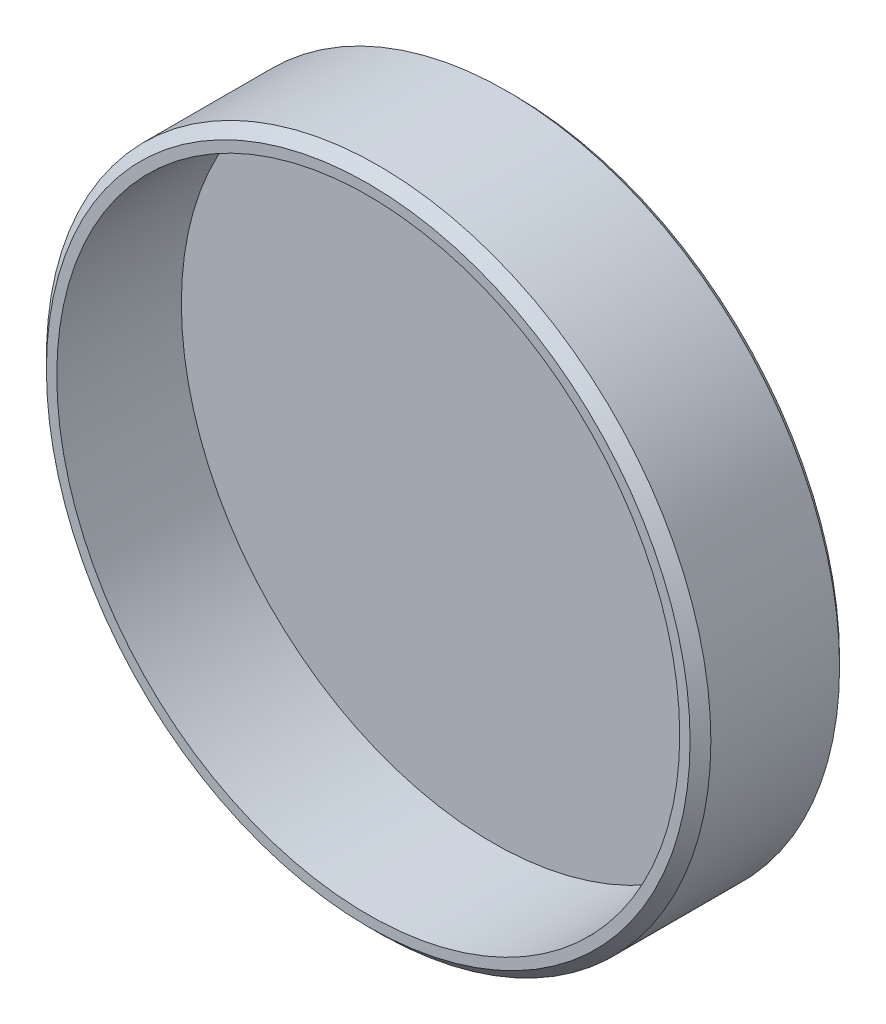
SolidWorks part; units mm, degrees
material "NBR"
ref_plane "Horní rovina" through (0, 0, 0) normal (0, 0, 1) x (1, 0, 0)
ref_plane "Přední rovina" through (0, 0, 0) normal (0, 1, 0) x (1, 0, 0)
ref_plane "Pravá rovina" through (0, 0, 0) normal (1, 0, 0) x (0, 0, -1)
sketch "Skica1" plane through (0, 0, 0) normal (0, 0, 1) x (1, 0, 0)
  circle A0 centre (0, 0) radius 16
  dimension "D1" = 32
extrude "Přidat vysunutím1" add sketch "Skica1" along normal blind 7
shell "Skořepina1" thickness 1
sketch "Skica2" plane through (0, 0, 0) normal (0, 0, -1) x (-1, 0, 0)
  circle A0 centre (0, 0) radius 13
  dimension "D1" = 26
extrude "Odebrat vysunutím1" cut sketch "Skica2" against normal blind 0.1
chamfer "Zkosení1" distance 0.5 angle 45 1 edges at (16, 0, 7)
chamfer "Zkosení2" distance 0.3 angle 45 1 edges at (16, 0, 0)
